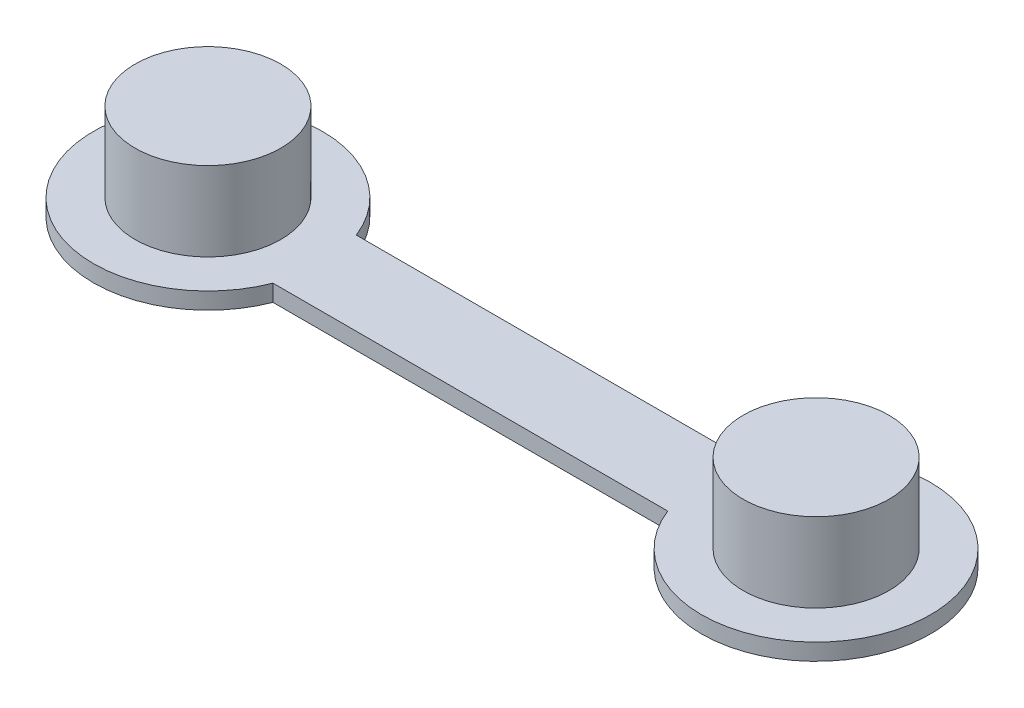
SolidWorks part; units mm, degrees
ref_plane "Front Plane" through (0, 0, 0) normal (0, 0, 1) x (1, 0, 0)
ref_plane "Top Plane" through (0, 0, 0) normal (0, 1, 0) x (1, 0, 0)
ref_plane "Right Plane" through (0, 0, 0) normal (1, 0, 0) x (0, 0, -1)
sketch "Sketch1" plane through (0, 0, 0) normal (0, 1, 0) x (1, 0, 0)
  line L0 (2.5617, 1) -> (12.0383, 1)
  line L1 (12.0383, -1) -> (2.5617, -1)
  arc A0 (2.5617, 1) -> (2.5617, -1) centre (0, 0) ccw
  arc A1 (12.0383, -1) -> (12.0383, 1) centre (14.6, 0) ccw
  dimension "D1" = 5.5
  dimension "D2" = 2
  dimension "D3" = 14.6
extrude "Boss-Extrude1" add sketch "Sketch1" along normal blind 0.4
sketch "Sketch2" plane through (0, 0.4, 0) normal (0, 1, 0) x (1, 0, 0)
  circle A0 centre (0, 0) radius 1.75
  circle A1 centre (14.6, 0) radius 1.75
  dimension "D1" = 3.5
extrude "Boss-Extrude2" add sketch "Sketch2" along normal blind 1.9
